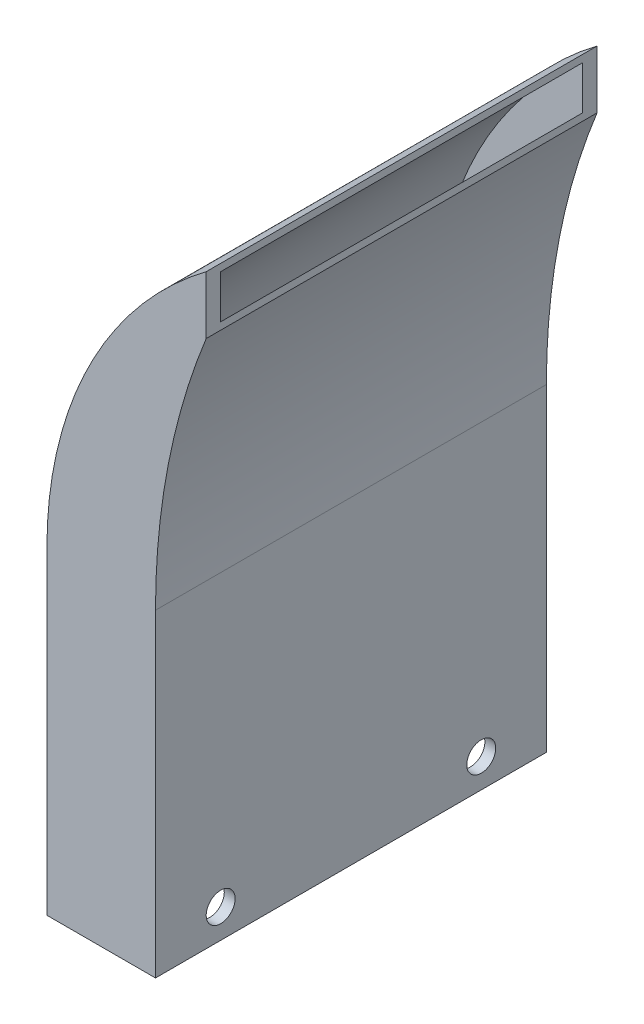
SolidWorks part; units mm, degrees
ref_plane "Front Plane" through (0, 0, 0) normal (0, 0, 1) x (1, 0, 0)
ref_plane "Top Plane" through (0, 0, 0) normal (0, 1, 0) x (1, 0, 0)
ref_plane "Right Plane" through (0, 0, 0) normal (1, 0, 0) x (0, 0, -1)
sketch "Sketch1" plane through (0, 0, 0) normal (0, 0, 1) x (1, 0, 0)
  line L0 (0, 0) -> (-11, 0) construction
  line L1 (-11, 0) -> (-11, 44) construction
  line L2 (-11, 44) -> (0, 44) construction
  line L3 (0, 44) -> (0, 40) construction
  line L4 (-11, 0) -> (-11, 22)
  line L5 (-11, 0) -> (-10.25, 0)
  line L6 (-10.25, 0) -> (-10.25, 22)
  line L8 (0, 40) -> (0, 0) construction
  line L9 (0, 44) -> (0, 43.5)
  line L10 (-11, 0) -> (-3.5, 0) construction
  line L11 (-3.5, 0) -> (-3.5, 22)
  line L12 (-3.5, 0) -> (-4.25, 0)
  line L13 (-4.25, 0) -> (-4.25, 22)
  line L14 (0, 40) -> (0, 40.5)
  arc A0 (-11, 22) -> (0, 44) centre (16.5, 22) cw
  arc A2 (-10.25, 22) -> (0, 43.5) centre (17.4238, 22) cw
  arc A3 (-3.5, 22) -> (0, 40) centre (44.5357, 22) cw
  arc A4 (-4.25, 22) -> (0, 40.5) centre (38.1397, 22) cw
  dimension "D1" = 11
  dimension "D2" = 44
  dimension "D3" = 11
  dimension "D4" = 22
  dimension "D5" = 0.75
  dimension "D6" = 22
  dimension "D7" = 0.5
  dimension "D8" = 4
  dimension "D9" = 7.5
  dimension "D10" = 22
  dimension "D11" = 22
  dimension "D12" = 0.75
  dimension "D13" = 0.5
extrude "Boss-Extrude1" add sketch "Sketch1" along normal blind 27
sketch "Sketch2" plane through (0, 0, 27) normal (0, 0, 1) x (1, 0, 0)
  line L0 (-4.25, 0) -> (-10.25, 0)
  line L1 (-10.25, 0) -> (-10.25, 22)
  line L2 (0, 43.5) -> (0, 40.5)
  line L3 (-4.25, 0) -> (-4.25, 22)
  arc A0 (-10.25, 22) -> (0, 43.5) centre (17.4238, 22) cw
  arc A1 (-4.25, 22) -> (0, 40.5) centre (38.1397, 22) cw
extrude "Boss-Extrude2" add sketch "Sketch2" against normal blind 1
sketch "Sketch3" plane through (0, 0, 0) normal (0, 0, -1) x (-1, 0, 0)
  line L0 (4.25, 0) -> (10.25, 0)
  line L1 (10.25, 0) -> (10.25, 22)
  line L2 (0, 43.5) -> (0, 40.5)
  line L3 (4.25, 0) -> (4.25, 22)
  arc A0 (10.25, 22) -> (0, 43.5) centre (-17.4238, 22) ccw
  arc A1 (4.25, 22) -> (0, 40.5) centre (-38.1397, 22) ccw
extrude "Boss-Extrude3" add sketch "Sketch3" against normal blind 1
sketch "Sketch4" plane through (-11, 0, 0) normal (-1, 0, 0) x (0, 0, 1)
  line L0 (4.5, 2) -> (22.5, 2) construction
  line L1 (13.5, 0) -> (13.5, 2) construction
  line L2 (27, 0) -> (0, 0) construction
  circle A0 centre (4.5, 2) radius 1
  circle A1 centre (22.5, 2) radius 1
  dimension "D5" = 2
  dimension "D6" = 2
  dimension "D1" = 2
  dimension "D2" = 18
  dimension "D3" = 9
  dimension "D4" = 2
extrude "Cut-Extrude1" cut sketch "Sketch4" against normal blind 15
